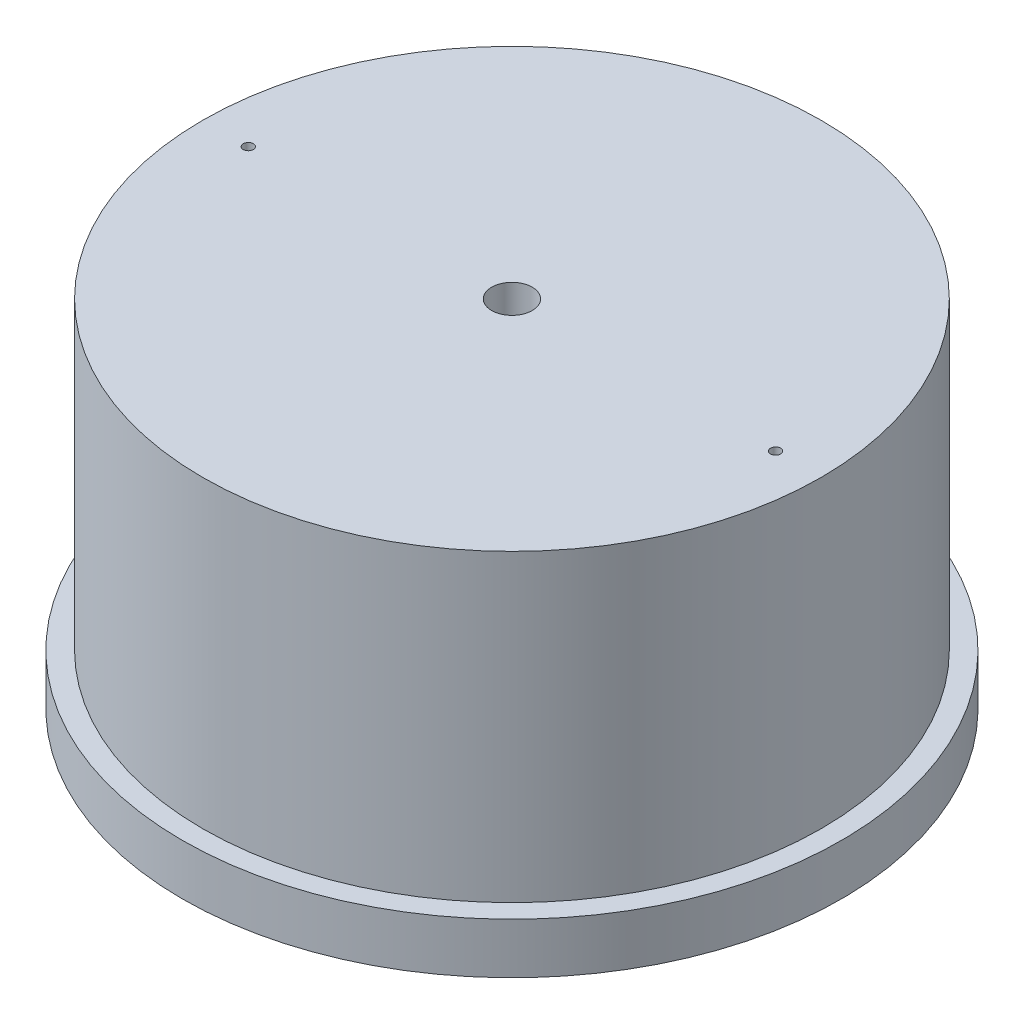
SolidWorks part; units mm, degrees
material "7075-T6 (SN)"
ref_plane "Front Plane" through (0, 0, 0) normal (0, 0, 1) x (1, 0, 0)
ref_plane "Top Plane" through (0, 0, 0) normal (0, 1, 0) x (1, 0, 0)
ref_plane "Right Plane" through (0, 0, 0) normal (1, 0, 0) x (0, 0, -1)
sketch "Sketch1" plane through (0, 0, 0) normal (0, 1, 0) x (1, 0, 0)
  circle A0 centre (0, 0) radius 32.5
extrude "Boss-Extrude1" add sketch "Sketch1" along normal blind 35
sketch "Sketch2" plane through (0, 35, 0) normal (0, 1, 0) x (1, 0, 0)
  circle A0 centre (0, 0) radius 30.5
  circle A1 centre (0, 0) radius 32.5
extrude "Cut-Extrude2" cut sketch "Sketch2" against normal blind 30
sketch "Sketch3" plane through (0, 0, 0) normal (0, -1, 0) x (1, 0, 0)
  circle A0 centre (0, 0) radius 24
  circle A1 centre (0, 0) radius 28
extrude "Cut-Extrude3" cut sketch "Sketch3" against normal blind 25
sketch "Sketch4" plane through (0, 0, 0) normal (0, -1, 0) x (1, 0, 0)
  circle A0 centre (0, 0) radius 18
extrude "Cut-Extrude4" cut sketch "Sketch4" against normal blind 20
sketch "Sketch5" plane through (0, 35, 0) normal (0, 1, 0) x (1, 0, 0)
  circle A0 centre (0, 0) radius 26 construction
  circle A1 centre (-26, 0) radius 0.5
  circle A2 centre (26, 0) radius 0.5
extrude "Cut-Extrude5" cut sketch "Sketch5" against normal through all
sketch "Sketch6" plane through (0, 35, 0) normal (0, 1, 0) x (1, 0, 0)
  circle A0 centre (0, 0) radius 2
extrude "Cut-Extrude6" cut sketch "Sketch6" against normal through all
